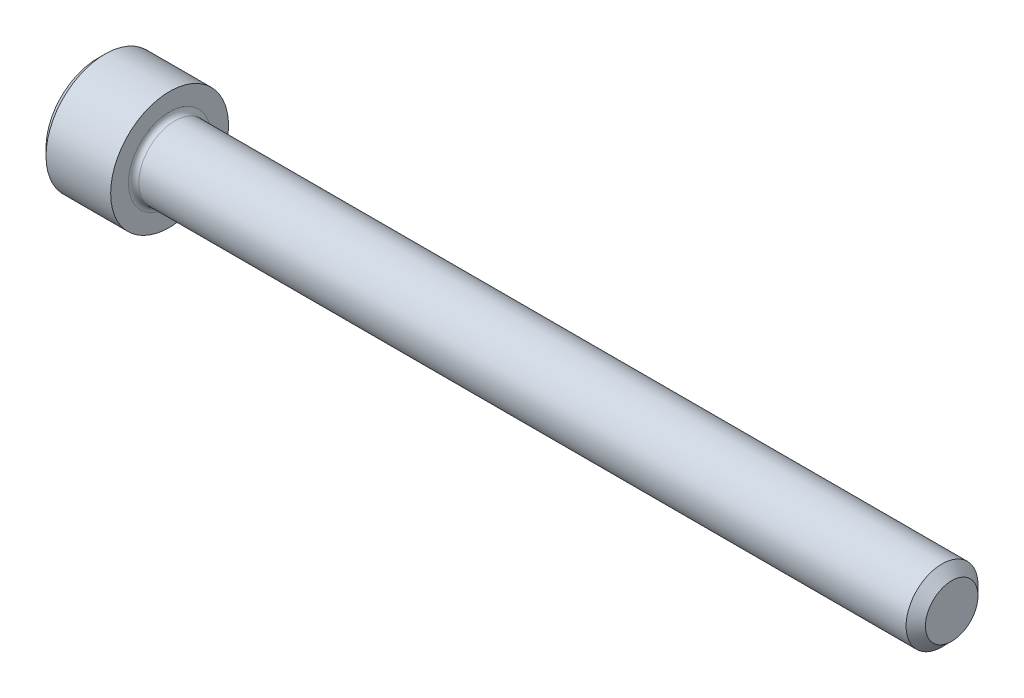
SolidWorks part; units mm, degrees
revolve "Base-Revolve" add sketch "BodySke" angle 360 about L6
sketch "BodySke" plane through (0, 0, 0) normal (0, 0, 1) x (1, 0, 0)
  line L0 (0, 0) -> (0, 2.5146)
  line L1 (0.3556, 2.8702) -> (3.5052, 2.8702)
  line L2 (3.5052, 2.8702) -> (3.5052, 1.7526)
  line L3 (3.5052, 1.7526) -> (41.1328, 1.7526)
  line L4 (41.6052, 1.2802) -> (41.6052, 0)
  line L5 (41.6052, 0) -> (0, 0)
  line L6 (-31.75, 0) -> (127, 0) construction
  line L7 (0, 2.5146) -> (0.3556, 2.8702)
  line L8 (41.6052, 1.2802) -> (41.1328, 1.7526)
  line L9 (0, -2.5146) -> (0.3556, -2.8702) construction
  line L10 (41.6052, -1.2802) -> (41.1328, -1.7526) construction
  line L11 (4.2977, 9.525) -> (4.2977, 3.175) construction
  line L12 (16.2052, 9.525) -> (16.2052, 3.175) construction
  line L13 (3.5052, 9.525) -> (3.5052, 3.175) construction
  dimension "Diameter" = 3.5052
  dimension "Head_ht" = 3.5052
  dimension "Length" = 38.1
  dimension "Body_ch_ang" = 45
  dimension "Head_dia" = 5.7404
  dimension "Head_ch_ang" = 45
  dimension "Head_side_ht" = 3.1496
  dimension "Minor_dia" = 2.5603
  dimension "Advance" = 0.7925
  dimension "Thread_nom" = 25.4
  dimension "Thread_length" = 38.1
cosmetic thread "ThreadCosmetic" parameters "Thread_length"=25.4, "Thread_minor"=2.5603
other "Defeature"
material "Alloy Steel"
ref_plane "Plane1" through (0, 0, 0) normal (0, 0, 1) x (1, 0, 0)
ref_plane "Plane2" through (0, 0, 0) normal (0, 1, 0) x (1, 0, 0)
ref_plane "Plane3" through (0, 0, 0) normal (1, 0, 0) x (0, 0, -1)
fillet "Fillet1" radius 0.254 1 edges at (3.5052, 0, 1.7526)
sketch "Sketch2" plane through (0, 0, 0) normal (0, 0, 1) x (1, 0, 0)
  line L0 (0, 1.3843) -> (1.6256, 1.3843)
  line L1 (1.6256, 1.3843) -> (2.4248, 0)
  line L2 (-31.75, 0) -> (127, 0) construction
  line L3 (2.4248, 0) -> (0, 0)
  line L4 (0, 0) -> (0, 1.3843)
  line L5 (0, 2.5146) -> (0, -2.5146) construction
  line L6 (0, 0) -> (47.625, 0) construction
  line L7 (3.5052, -2.8702) -> (3.5052, 2.8702) construction
  dimension "D1" = 1.3843
  dimension "D2" = 60
revolve "Hex-PreBroach" cut sketch "Sketch2" angle 360 about L6
sketch "Sketch3" plane through (0, 0, 0) normal (-1, 0, 0) x (0, 0.5, 0.866)
  line L0 (0.7992, 1.3843) -> (-0.7992, 1.3843)
  line L1 (-0.7992, 1.3843) -> (-1.5985, 0)
  line L2 (0.7992, 1.3843) -> (1.5985, 0)
  line L3 (0.7992, -1.3843) -> (1.5985, 0)
  line L4 (0.7992, -1.3843) -> (-0.7992, -1.3843)
  line L5 (-0.7992, -1.3843) -> (-1.5985, 0)
  dimension "D1" = 1.3843
  dimension "D2" = 1.3843
  dimension "Hex_size" = 2.7686
extrude "Hex" cut sketch "Sketch3" against normal blind 1.6256
sketch "Sketch4" plane through (0, 0, 0) normal (-1, 0, 0) x (0, 0, 1)
  line L0 (0, 0) -> (1.7399, 0)
  line L1 (0, 0) -> (6.1484, 3.5498) construction
  line L2 (0, 0) -> (0.8699, 1.5068)
  line L3 (1.4457, 0.3947) -> (1.6607, 0.5189)
  line L4 (1.0647, 1.0546) -> (1.2797, 1.1788)
  arc A0 (1.4457, 0.3947) -> (1.0647, 1.0546) centre (0, 0) ccw
  arc A1 (1.7399, 0) -> (1.6607, 0.5189) centre (0, 0) ccw
  arc A2 (0.8699, 1.5068) -> (1.2797, 1.1788) centre (0, 0) cw
  dimension "D1" = 30
  dimension "D2" = 60
  dimension "Spline_p_dim" = 0.762
  dimension "D3" = 0.381
extrude "Spline" [suppressed] cut sketch "Sketch4" against normal blind 1.6256
pattern_circular "CirPattern1" [suppressed] count 6 every 60 about axis through (-31.75, 0, 0) along (1, 0, 0)
sketch "Sketch5" plane through (0, 0, 0) normal (0, 0, 1) x (1, 0, 0)
  line L0 (-31.75, 0) -> (127, 0) construction
  line L2 (0, 2.5146) -> (0, -2.5146) construction
  circle A0 centre (1.27, 0) radius 0.4445
  dimension "Drilled_hole_dia" = 0.889
  dimension "Drilled_hole_loc" = 1.27
extrude "Hole" [suppressed] cut sketch "Sketch5" against normal through all and the other way through all
pattern_circular "Drilled-4" [suppressed] count 2 every 60 about axis through (-31.75, 0, 0) along (1, 0, 0)
pattern_circular "Drilled-6" [suppressed] count 3 every 60 about axis through (-31.75, 0, 0) along (1, 0, 0)
sketch "ThdSchSke" plane through (0, 0, 0) normal (0, 0, 1) x (1, 0, 0)
  line L0 (16.2052, -1.2802) -> (15.8744, -1.7526)
  line L1 (16.2052, -1.2802) -> (16.536, -1.7526)
  line L2 (16.536, -1.7526) -> (16.536, -2.1908)
  line L3 (-3.175, 0) -> (5.1513, 0) construction
  line L5 (16.536, -2.1908) -> (15.8744, -2.1908)
  line L6 (15.8744, -2.1908) -> (15.8744, -1.7526)
  line L7 (0, 2.5146) -> (0, -2.5146) construction
  dimension "Thread_minor" = 2.5603
  dimension "Diameter" = 3.5052
  dimension "Start" = 16.2052
revolve "ThreadSchematic" [suppressed] cut sketch "ThdSchSke" angle 360 about L3
pattern_linear "ThdSchPat" [suppressed]
equation "\"D2@Sketch3\" = \"Hex_size@Sketch3\" / 2"
equation "\"D1@Sketch3\" = \"Hex_size@Sketch3\" / 2"
equation "\"D1@Sketch2\" = \"Hex_size@Sketch3\" / 2"
equation "\"D3@Sketch4\" = \"Spline_p_dim@Sketch4\" / 2"
equation "\"Thread_minor@ThreadCosmetic\"  =  \"Minor_dia@BodySke\""
equation "\"D2@CirPattern1\" = 360 / \"Num_teeth@CirPattern1\""
equation "\"Wall_thickness@Sketch2\" = \"Head_ht@BodySke\" - \"Key_eng@Hex\""
equation "\"Thread_length@ThreadCosmetic\" = ((sgn( (\"Length@BodySke\" - \"Advance@BodySke\" ) - \"Thread_nom@BodySke\" )-1)*( (\"Length@BodySke\" - \"Advance@BodySke\" ) - \"Thread_nom@BodySke\" ))/-2+ \"Thread_nom@BodySke\""
equation "\"Thread_minor@ThdSchSke\" = \"Minor_dia@BodySke\""
equation "\"Diameter@ThdSchSke\" = \"Diameter@BodySke\""
equation "\"Overcut@ThdSchSke\" = \"Diameter@BodySke\" * 1.25"
equation "\"Start@ThdSchSke\" = \"Head_ht@BodySke\" + \"Length@BodySke\" - \"Thread_length@ThreadCosmetic\"  '---Non-countersunk---"
equation "\"Num_threads@ThdSchPat\" = int( \"Thread_length@ThreadCosmetic\" / \"Advance@BodySke\" + 0.999 )  + 1"
equation "\"Advance@ThdSchPat\" = \"Thread_length@ThreadCosmetic\" /  (\"Num_threads@ThdSchPat\" - 1) 'relax it"
equation "\"Num_threads@ThdSchPat\" = \"Num_threads@ThdSchPat\" - sgn( \"Num_threads@ThdSchPat\" - 1) '---chamfered tips only---"
